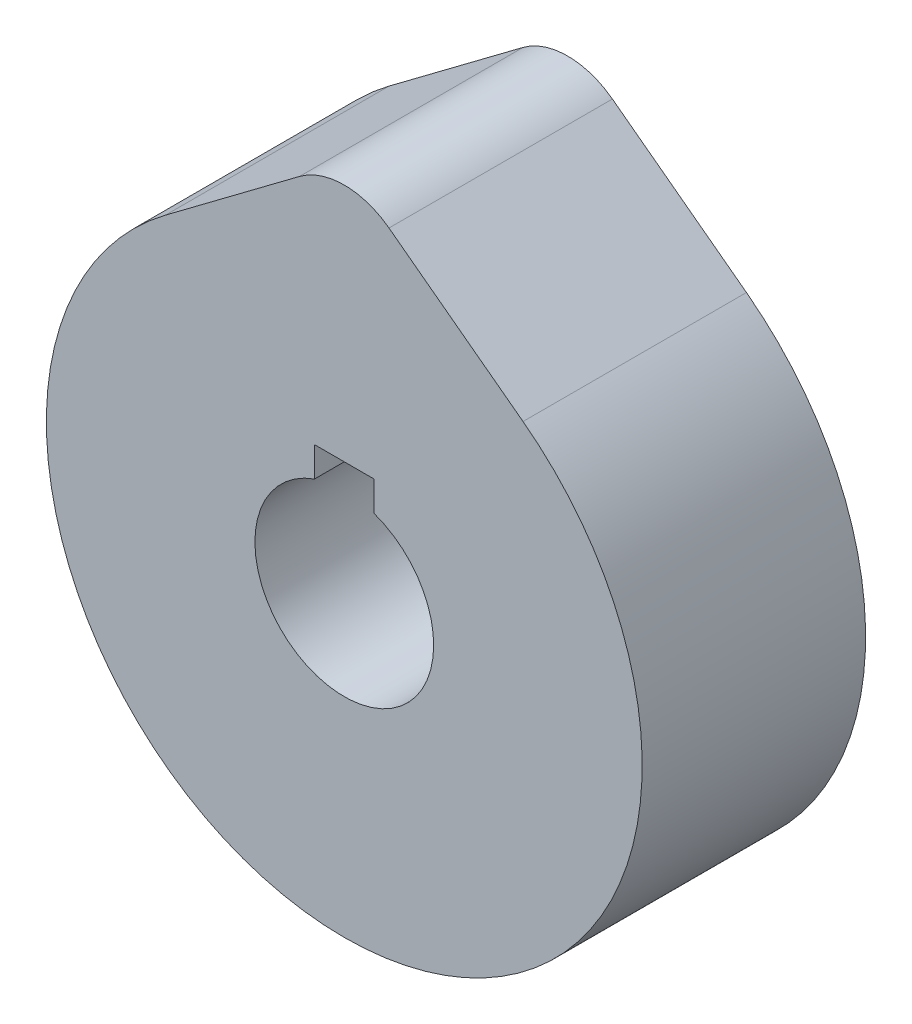
SolidWorks part; units mm, degrees
ref_plane "Front Plane" through (0, 0, 0) normal (0, 0, 1) x (1, 0, 0)
ref_plane "Top Plane" through (0, 0, 0) normal (0, 1, 0) x (1, 0, 0)
ref_plane "Right Plane" through (0, 0, 0) normal (1, 0, 0) x (0, 0, -1)
sketch "Sketch1" plane through (0, 0, 0) normal (0, 0, 1) x (1, 0, 0)
  line L0 (-3, 22.75) -> (-12, 16)
  line L1 (3, 22.75) -> (12, 16)
  line L2 (0, 11.3059) -> (0, -12.2424) construction
  line L3 (2, 7.6569) -> (-2, 7.6569)
  line L4 (-2, 7.6569) -> (-2, 5.6569)
  line L5 (2, 7.6569) -> (2, 5.6569)
  arc A0 (-12, 16) -> (12, 16) centre (0, 0) ccw
  arc A1 (-3, 22.75) -> (3, 22.75) centre (0, 18.75) cw
  arc A2 (-2, 5.6569) -> (2, 5.6569) centre (0, 0) ccw
  point P15 (0, 7.6569)
  dimension "D1" = 40
  dimension "D3" = 2
  dimension "D4" = 2
  dimension "D2" = 5
  dimension "D5" = 12
extrude "Boss-Extrude1" add sketch "Sketch1" along normal blind 15
